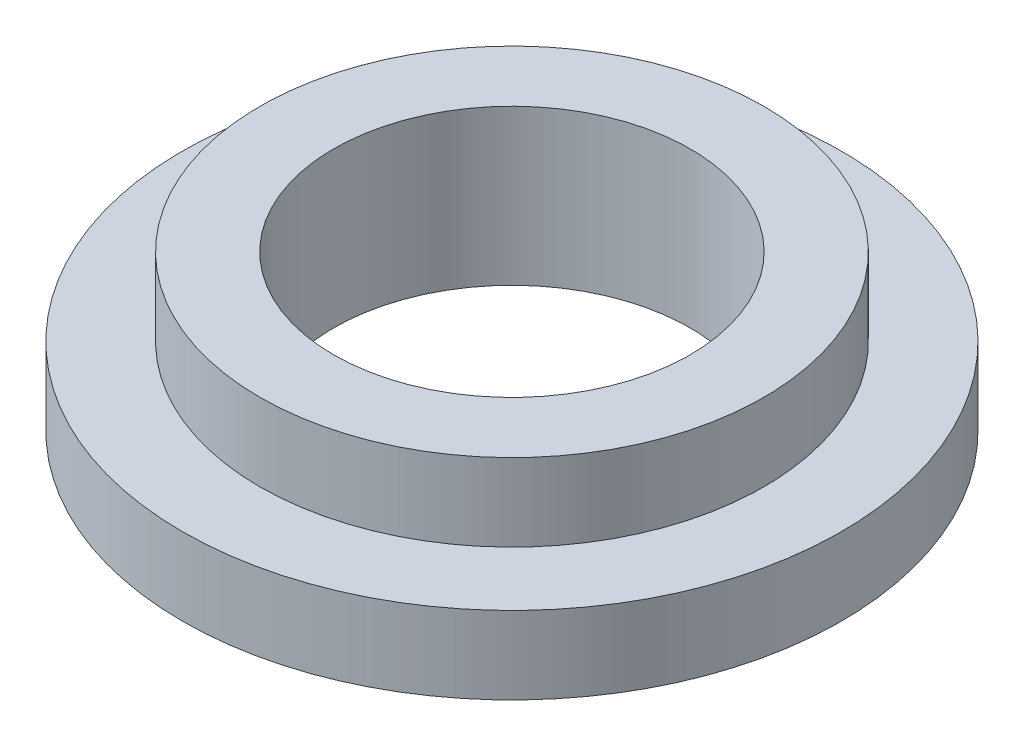
SolidWorks part; units mm, degrees
ref_plane "Front Plane" through (0, 0, 0) normal (0, 0, 1) x (1, 0, 0)
ref_plane "Top Plane" through (0, 0, 0) normal (0, 1, 0) x (1, 0, 0)
ref_plane "Right Plane" through (0, 0, 0) normal (1, 0, 0) x (0, 0, -1)
sketch "Sketch1" plane through (0, 0, 0) normal (0, 1, 0) x (1, 0, 0)
  circle A0 centre (0, 0) radius 42.5
extrude "Boss-Extrude1" add sketch "Sketch1" along normal blind 10
sketch "Sketch2" plane through (0, 10, 0) normal (0, 1, 0) x (1, 0, 0)
  circle A0 centre (0, 0) radius 32.5
extrude "Boss-Extrude2" add sketch "Sketch2" along normal blind 10
sketch "Sketch3" plane through (0, 20, 0) normal (0, 1, 0) x (1, 0, 0)
  circle A0 centre (0, 0) radius 23
extrude "Cut-Extrude1" cut sketch "Sketch3" against normal through all
